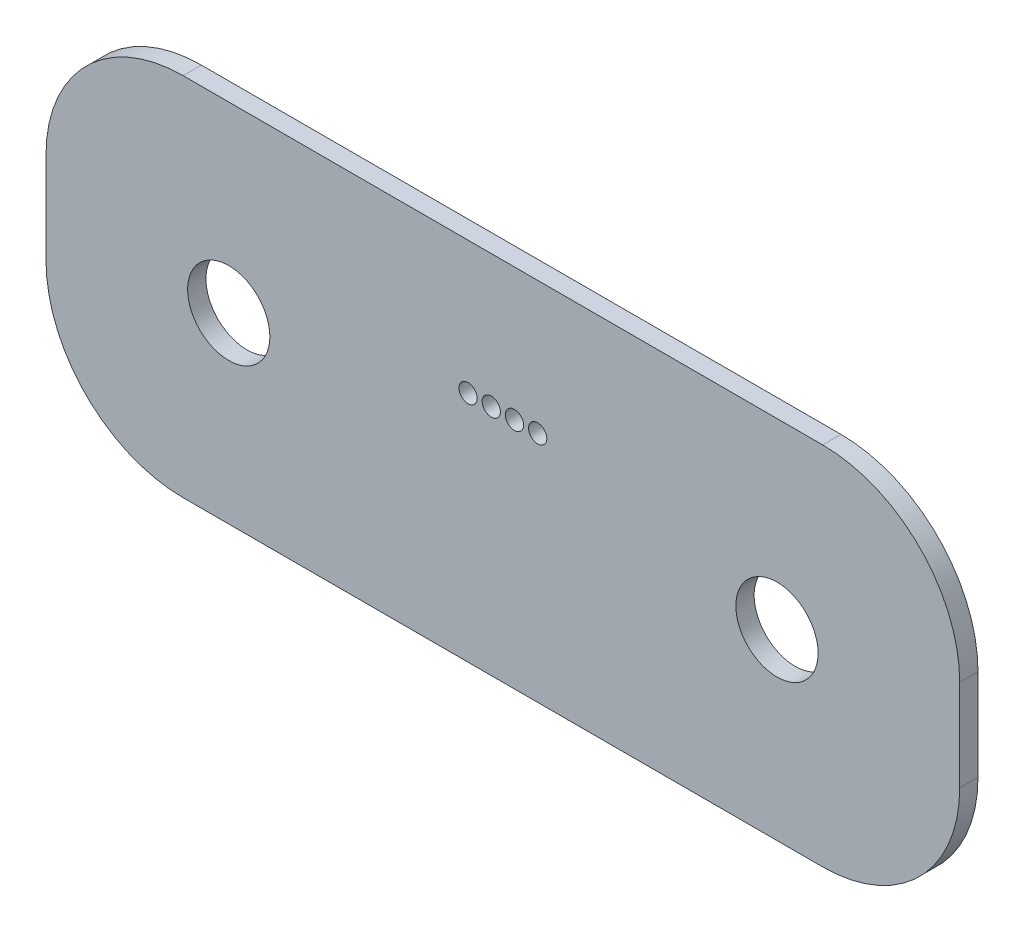
SolidWorks part; units mm, degrees
ref_plane "Front Plane" through (0, 0, 0) normal (0, 0, 1) x (1, 0, 0)
ref_plane "Top Plane" through (0, 0, 0) normal (0, 1, 0) x (1, 0, 0)
ref_plane "Right Plane" through (0, 0, 0) normal (1, 0, 0) x (0, 0, -1)
sketch "Sketch1" plane through (0, 0, 0) normal (0, 0, 1) x (1, 0, 0)
  line L0 (-25, 2.5) -> (-25, -2.5)
  line L1 (-17.5, -10) -> (17.5, -10)
  line L2 (25, -2.5) -> (25, 2.5)
  line L3 (17.5, 10) -> (-17.5, 10)
  line L4 (-15, 0) -> (15, 0) construction
  line L5 (-1.905, 2.75) -> (1.905, 2.75) construction
  line L6 (0, 0) -> (0, 5.5) construction
  circle A0 centre (-15, 0) radius 2.25
  circle A1 centre (15, 0) radius 2.25
  circle A2 centre (-1.905, 2.75) radius 0.5
  circle A3 centre (1.905, 2.75) radius 0.5
  circle A4 centre (0.635, 2.75) radius 0.5
  circle A5 centre (-0.635, 2.75) radius 0.5
  arc A6 (-25, 2.5) -> (-17.5, 10) centre (-17.5, 2.5) cw
  arc A7 (-25, -2.5) -> (-17.5, -10) centre (-17.5, -2.5) ccw
  arc A8 (17.5, -10) -> (25, -2.5) centre (17.5, -2.5) ccw
  arc A9 (25, 2.5) -> (17.5, 10) centre (17.5, 2.5) ccw
  point P8 (0, 0)
  point P14 (0, 2.75)
  dimension "D5" = 4.5
  dimension "D10" = 1
  dimension "D12" = 7.5
  dimension "D13" = 7.5
  dimension "D14" = 7.5
  dimension "D15" = 7.5
  dimension "D1" = 10
  dimension "D2" = 10
  dimension "D3" = 10
  dimension "D4" = 10
  dimension "D6" = 30
  dimension "D7" = 12.75
  dimension "D8" = 3.81
  dimension "D9" = 1.27
  dimension "D11" = 1.27
extrude "Boss-Extrude1" add sketch "Sketch1" along normal blind 1
